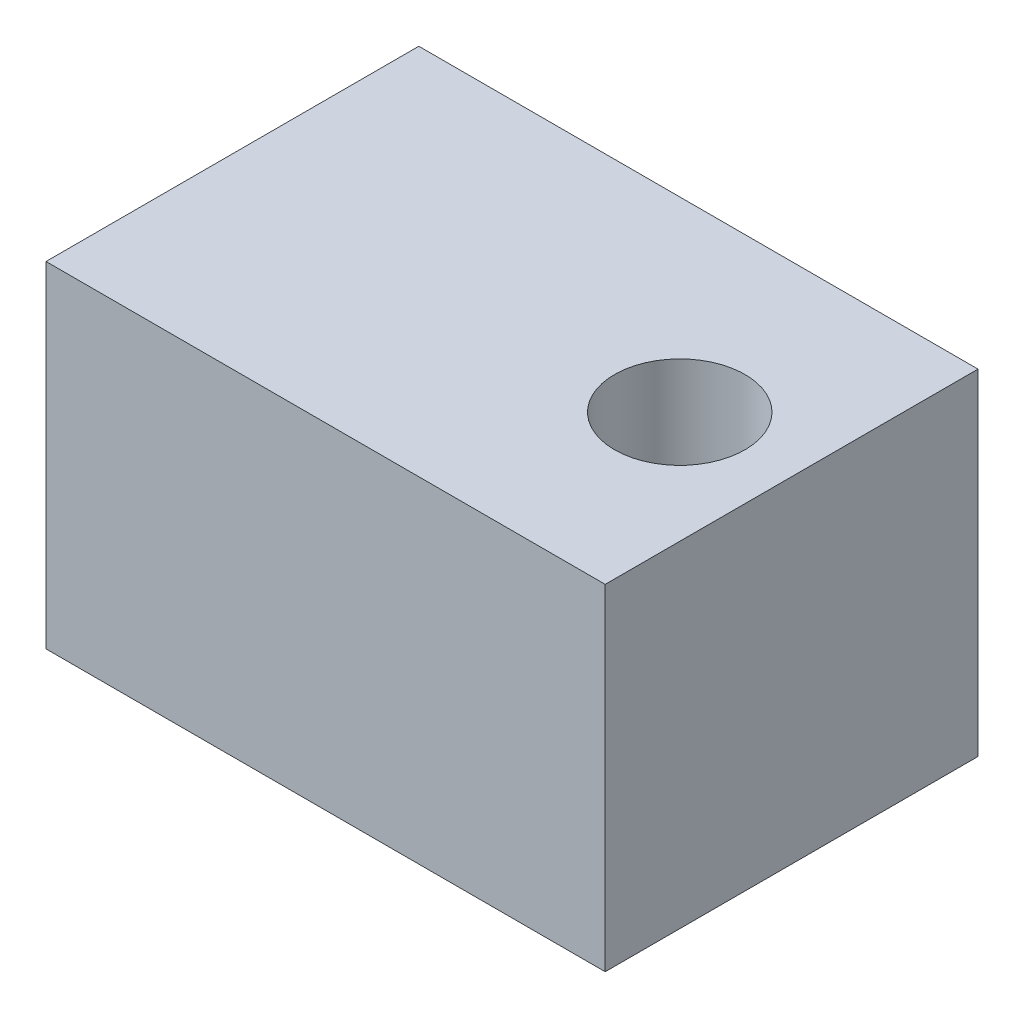
SolidWorks part; units mm, degrees
material "ABS"
ref_plane "Front Plane" through (0, 0, 0) normal (0, 0, 1) x (1, 0, 0)
ref_plane "Top Plane" through (0, 0, 0) normal (0, 1, 0) x (1, 0, 0)
ref_plane "Right Plane" through (0, 0, 0) normal (1, 0, 0) x (0, 0, -1)
sketch "Sketch1" plane through (0, 0, 0) normal (0, 1, 0) x (1, 0, 0)
  line L5 (-7.5, -5) -> (7.5, -5)
  line L6 (-7.5, -5) -> (-7.5, 5)
  line L7 (-7.5, 5) -> (7.5, 5)
  line L8 (7.5, -5) -> (7.5, 5)
  line L9 (-7.5, -5) -> (7.5, 5) construction
  line L10 (-7.5, 5) -> (7.5, -5) construction
  point P1 (0, 0)
  point P7 (0, 0)
  dimension "D1" = 15
  dimension "D2" = 10
extrude "Boss-Extrude1" add sketch "Sketch1" along normal blind 9
sketch "Sketch3" plane through (0, 9, 0) normal (0, 1, 0) x (1, 0, 0)
  line L0 (7.5, -5) -> (7.5, 5) construction
  circle A0 centre (4.5, 0) radius 1.75
  dimension "D1" = 3.5
  dimension "D2" = 3
extrude "Cut-Extrude1" cut sketch "Sketch3" against normal through all
